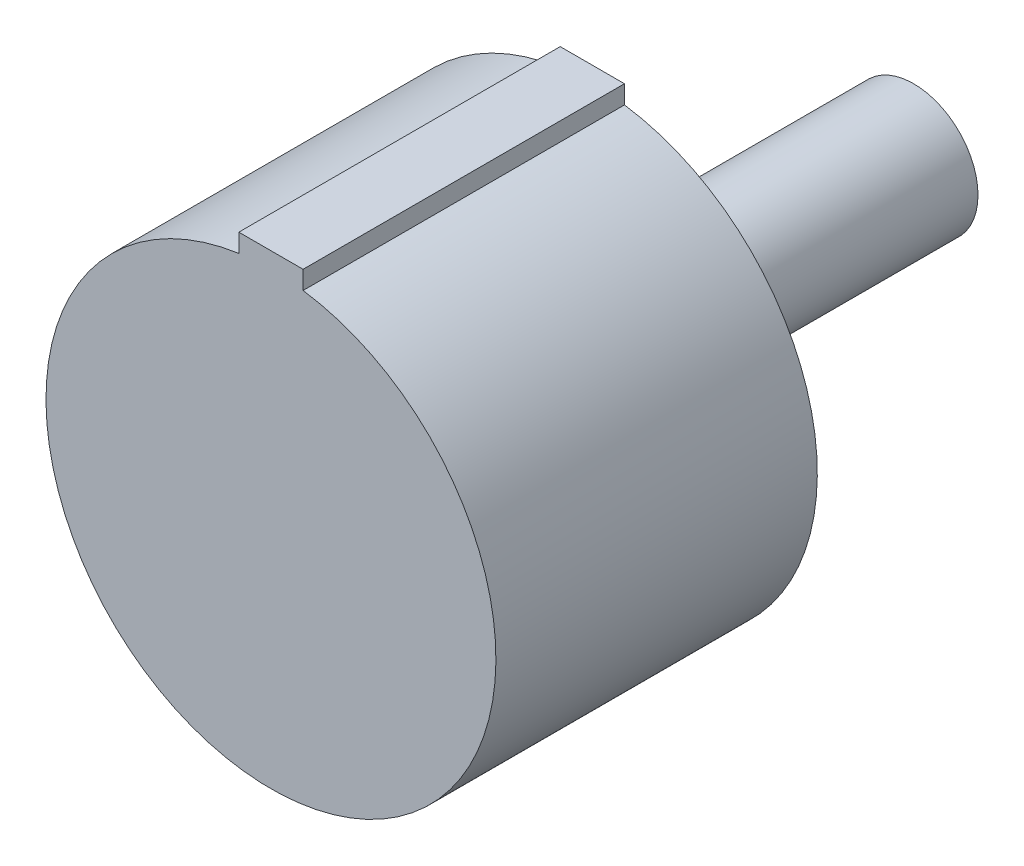
SolidWorks part; units mm, degrees
ref_plane "Front Plane" through (0, 0, 0) normal (0, 0, 1) x (1, 0, 0)
ref_plane "Top Plane" through (0, 0, 0) normal (0, 1, 0) x (1, 0, 0)
ref_plane "Right Plane" through (0, 0, 0) normal (1, 0, 0) x (0, 0, -1)
sketch "Sketch1" plane through (0, 0, 0) normal (0, 0, 1) x (1, 0, 0)
  circle A0 centre (0, 0) radius 4
  dimension "D1" = 8
extrude "Boss-Extrude1" add sketch "Sketch1" along normal blind 40
sketch "Sketch2" plane through (0, 0, 40) normal (0, 0, 1) x (1, 0, 0)
  line L0 (-2, 13.8564) -> (-2, 15)
  line L1 (-2, 15) -> (2, 15)
  line L2 (2, 15) -> (2, 13.8564)
  arc A0 (-2, 13.8564) -> (2, 13.8564) centre (0, 0) ccw
  dimension "D1" = 28
  dimension "D2" = 2
  dimension "D3" = 2
  dimension "D4" = 15
extrude "Boss-Extrude2" add sketch "Sketch2" against normal blind 20
